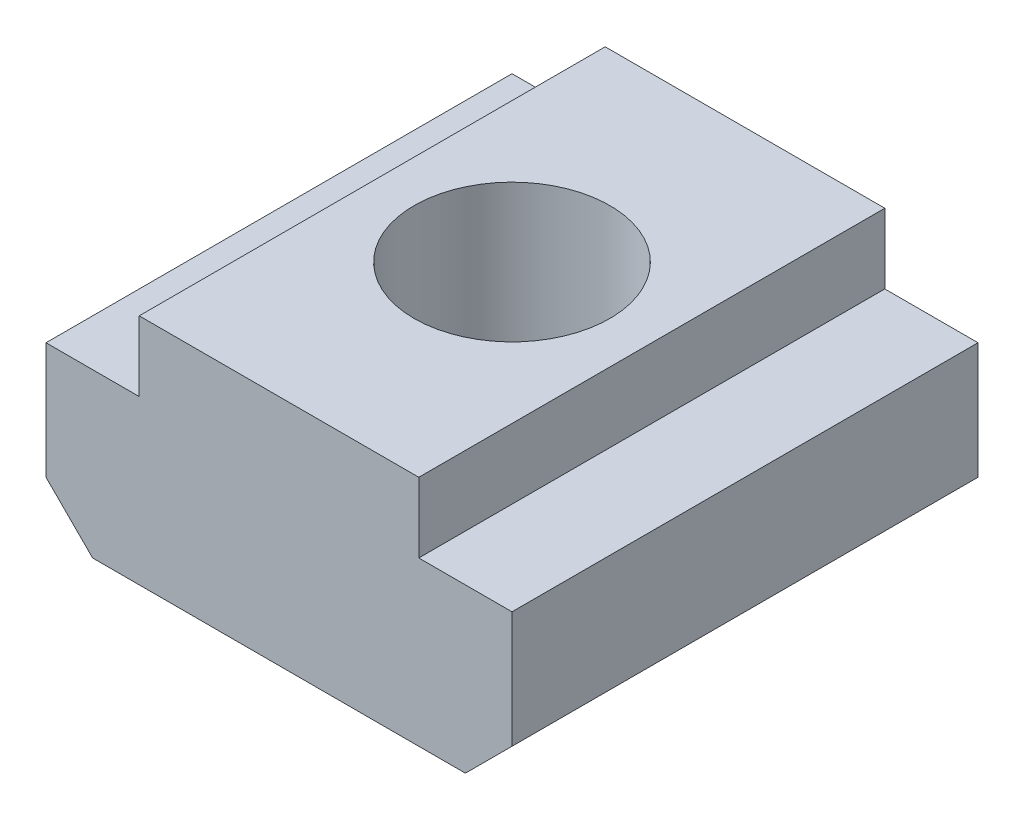
SolidWorks part; units mm, degrees
ref_plane "Front Plane" through (0, 0, 0) normal (0, 0, 1) x (1, 0, 0)
ref_plane "Top Plane" through (0, 0, 0) normal (0, 1, 0) x (1, 0, 0)
ref_plane "Right Plane" through (0, 0, 0) normal (1, 0, 0) x (0, 0, -1)
sketch "Sketch1" plane through (0, 0, 0) normal (0, 0, 1) x (1, 0, 0)
  line L0 (0, 0) -> (0, 46.9655) construction
  line L1 (-4, 0) -> (4, 0)
  line L2 (4, 0) -> (5, 1)
  line L3 (5, 1) -> (5, 3.5)
  line L4 (5, 3.5) -> (3, 3.5)
  line L5 (3, 3.5) -> (3, 5)
  line L6 (3, 5) -> (-3, 5)
  line L7 (-3, 5) -> (-3, 3.5)
  line L8 (-3, 3.5) -> (-5, 3.5)
  line L9 (-5, 3.5) -> (-5, 1)
  line L10 (-5, 1) -> (-4, 0)
  point P10 (0, 5)
  point P14 (-5, 2.25)
  dimension "D1" = 6
  dimension "D2" = 10
  dimension "D3" = 5
  dimension "D4" = 1.5
  dimension "D5" = 5
  dimension "D6" = 1
  dimension "D7" = 1
  dimension "D8" = 1
extrude "Boss-Extrude1" add sketch "Sketch1" along normal blind 10
sketch "Sketch2" plane through (0, 5, 0) normal (0, 1, 0) x (1, 0, 0)
  line L0 (-3, 0) -> (3, -10) construction
  point P4 (0, -5)
hole_wizard "M5x0.8 Tapped Hole1" positions "Sketch3" profile "Sketch4" tap size "M5x0.8" standard "ANSI Metric" end condition through all
sketch "Sketch3" plane through (0, 5, 0) normal (0, 1, 0) x (1, 0, 0)
  point P0 (0, -5)
sketch "Sketch4" plane through (0, 5, 5) normal (1, 0, 0) x (0, 0, 1)
  line L0 (0, 0) -> (0, 5)
  line L1 (0, 5) -> (2.1, 5)
  line L2 (2.1, 5) -> (2.1, 0)
  line L5 (2.1, 0) -> (0, 0)
  line L11 (0, -6.35) -> (0, 107.95) construction
  dimension "Thru Tap Drill Dia." = 4.2
  dimension "Thru Tap Drill Depth" = 5
cosmetic thread "Hole Thread1" parameters "D2"=5
